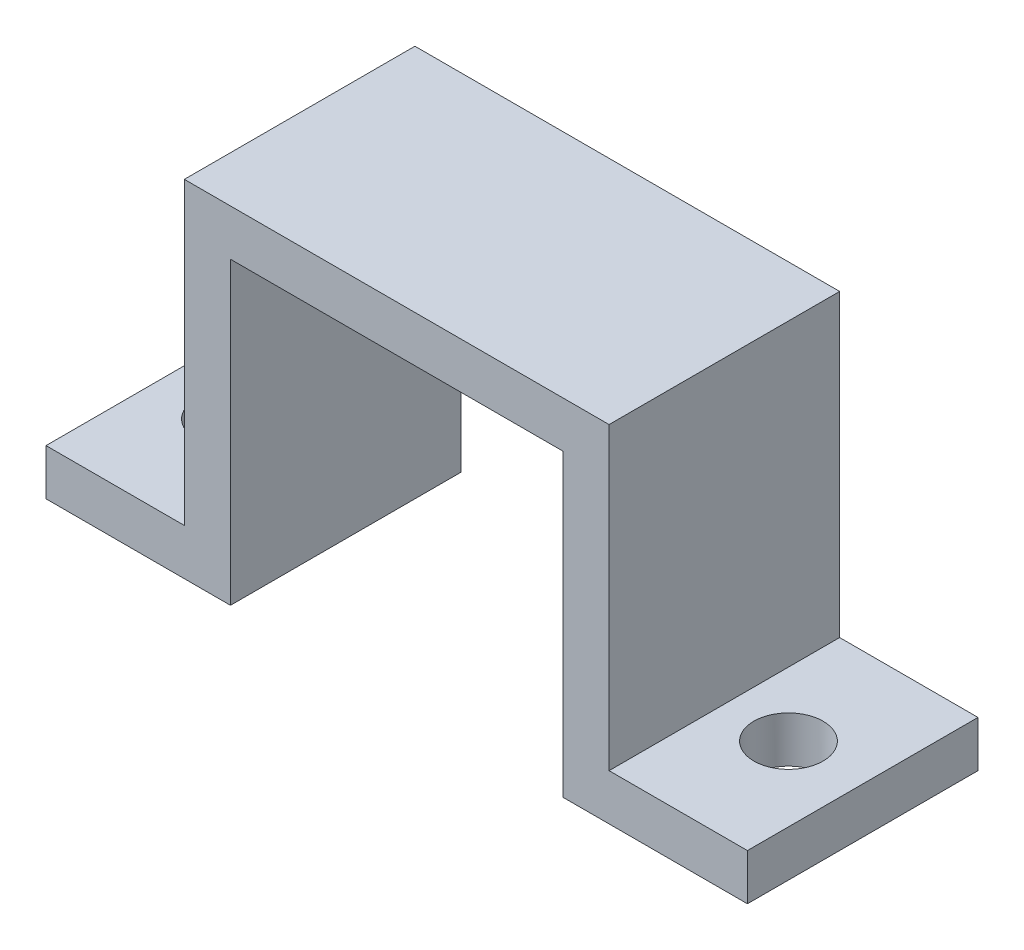
SolidWorks part; units mm, degrees
ref_plane "Front Plane" through (0, 0, 0) normal (0, 0, 1) x (1, 0, 0)
ref_plane "Top Plane" through (0, 0, 0) normal (0, 1, 0) x (1, 0, 0)
ref_plane "Right Plane" through (0, 0, 0) normal (1, 0, 0) x (0, 0, -1)
sketch "Sketch1" plane through (0, 0, 0) normal (0, 0, 1) x (1, 0, 0)
  line L0 (-16.0884, -3.521) -> (-16.0884, -1.521)
  line L1 (-16.0884, -1.521) -> (-10.0884, -1.521)
  line L2 (-10.0884, -1.521) -> (-10.0884, 11.479)
  line L3 (-10.0884, 11.479) -> (8.3316, 11.479)
  line L4 (8.3316, 11.479) -> (8.3316, -1.521)
  line L5 (8.3316, -1.521) -> (14.3316, -1.521)
  line L6 (14.3316, -1.521) -> (14.3316, -3.521)
  line L7 (14.3316, -3.521) -> (6.3316, -3.521)
  line L8 (6.3316, -3.521) -> (6.3316, 9.479)
  line L9 (6.3316, 9.479) -> (-8.0884, 9.479)
  line L10 (-8.0884, 9.479) -> (-8.0884, -3.521)
  line L11 (-8.0884, -3.521) -> (-16.0884, -3.521)
  dimension "D1" = 13
  dimension "D2" = 2
  dimension "D3" = 2
  dimension "D4" = 2
  dimension "D5" = 2
  dimension "D6" = 2
  dimension "D7" = 6
  dimension "D8" = 6
  dimension "D9" = 14.42
  dimension "D10" = 13
  dimension "D11" = 13
extrude "Boss-Extrude1" add sketch "Sketch1" along normal blind 10
sketch "Sketch2" plane through (0, -1.521, 0) normal (0, 1, 0) x (1, 0, 0)
  line L0 (-10.0884, 0) -> (-16.0884, 0) construction
  line L2 (14.3316, 0) -> (8.3316, 0) construction
  line L3 (-10.0884, -10) -> (-10.0884, 0) construction
  circle A0 centre (-13.0884, -5) radius 1.5
  circle A1 centre (11.1121, -5) radius 1.5
  dimension "D1" = 3
  dimension "D2" = 3
  dimension "D3" = 5
  dimension "D4" = 5
  dimension "D5" = 3
extrude "Cut-Extrude1" cut sketch "Sketch2" against normal through all both and the other way through all
